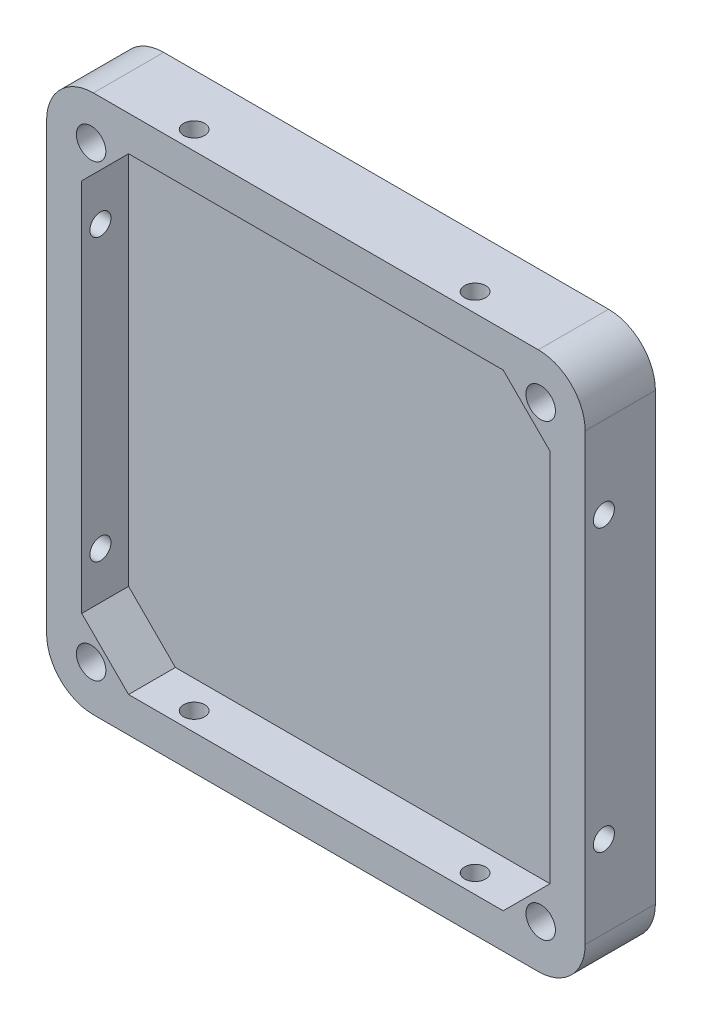
SolidWorks part; units mm, degrees
ref_plane "Front Plane" through (0, 0, 0) normal (0, 0, 1) x (1, 0, 0)
ref_plane "Top Plane" through (0, 0, 0) normal (0, 1, 0) x (1, 0, 0)
ref_plane "Right Plane" through (0, 0, 0) normal (1, 0, 0) x (0, 0, -1)
sketch "Sketch1" plane through (0, 0, 0) normal (0, 0, 1) x (1, 0, 0)
  line L1 (57.5, -57.5) -> (-57.5, -57.5)
  line L2 (57.5, -57.5) -> (57.5, 57.5)
  line L3 (57.5, 57.5) -> (-57.5, 57.5)
  line L4 (-57.5, -57.5) -> (-57.5, 57.5)
  line L5 (57.5, -57.5) -> (-57.5, 57.5) construction
  line L6 (57.5, 57.5) -> (-57.5, -57.5) construction
  point P0 (0, 0)
  dimension "D1" = 115
  dimension "D2" = 115
extrude "Boss-Extrude1" add sketch "Sketch1" along normal mid plane 15
fillet "Fillet1" radius 10 4 edges at (-57.5, -57.5, 0) (57.5, -57.5, 0) (-57.5, 57.5, 0) (57.5, 57.5, 0)
ref_plane "Plane1" through (0, 0, 7.5) normal (0, 0, 1) x (1, 0, 0)
sketch "Sketch2" plane through (0, 0, 7.5) normal (0, 0, 1) x (1, 0, 0)
  line L1 (50, -50) -> (-50, -50)
  line L2 (50, -50) -> (50, 50)
  line L3 (50, 50) -> (-50, 50)
  line L4 (-50, -50) -> (-50, 50)
  line L5 (50, -50) -> (-50, 50) construction
  line L6 (50, 50) -> (-50, -50) construction
  point P0 (0, 0)
  dimension "D1" = 100
  dimension "D2" = 100
extrude "Cut-Extrude1" cut sketch "Sketch2" against normal blind 10
fillet "Fillet2" [suppressed] radius 10
chamfer "Chamfer1" distance 10 angle 45 4 edges at (-50, -50, 2.5) (50, -50, 2.5) (50, 50, 2.5) (-50, 50, 2.5)
sketch "Sketch3" plane through (0, 0, 7.5) normal (0, 0, 1) x (1, 0, 0)
  circle A0 centre (-48, 48) radius 3.15
  dimension "D1" = 6.3
  dimension "D2" = 48
  dimension "D3" = 48
extrude "Cut-Extrude2" cut sketch "Sketch3" against normal blind 30
mirror "Mirror1" about plane through (0, 0, 0) normal (1, 0, 0) of "Cut-Extrude2" second plane through (0, 0, 0) second plane normal (0, 1, 0)
ref_plane "Plane2" through (57.5, 0, 0) normal (1, 0, 0) x (0, 0, -1)
sketch "Sketch4" plane through (57.5, 0, 0) normal (1, 0, 0) x (0, 0, -1)
  circle A0 centre (-3.5, 30) radius 2.25
  dimension "D1" = 4.5
  dimension "D2" = 3.5
  dimension "D3" = 30
extrude "Cut-Extrude3" cut sketch "Sketch4" against normal blind 130
mirror "Mirror2" about plane through (0, 0, 0) normal (0, 1, 0) of "Cut-Extrude3"
ref_plane "Plane3" through (0, 57.5, 0) normal (0, 1, 0) x (1, 0, 0)
sketch "Sketch6" plane through (0, 57.5, 0) normal (0, 1, 0) x (1, 0, 0)
  circle A0 centre (-30, -3.5) radius 2.25
  dimension "D1" = 4.5
  dimension "D2" = 3.5
  dimension "D3" = 30
extrude "Cut-Extrude4" cut sketch "Sketch6" against normal through all
mirror "Mirror3" about plane through (0, 0, 0) normal (1, 0, 0) of "Cut-Extrude4"
